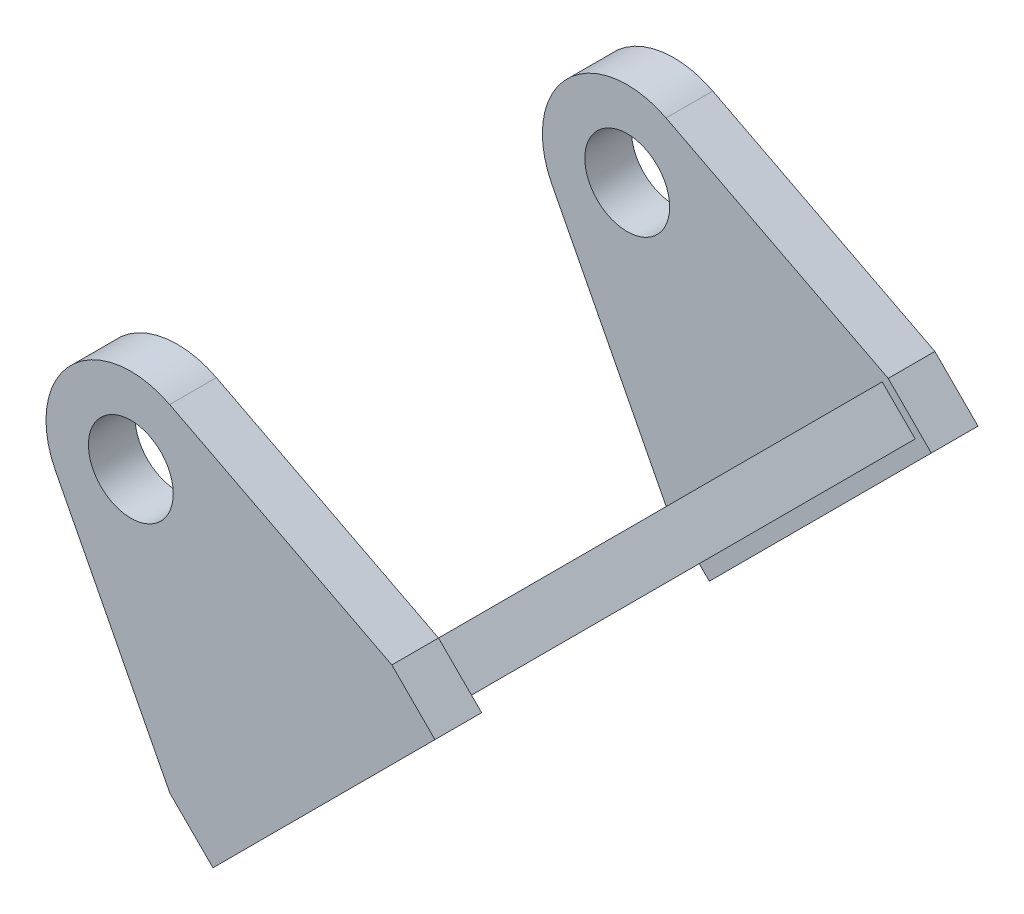
SolidWorks part; units mm, degrees
ref_plane "正面" through (0, 0, 0) normal (0, 0, 1) x (1, 0, 0)
ref_plane "平面" through (0, 0, 0) normal (0, 1, 0) x (1, 0, 0)
ref_plane "右側面" through (0, 0, 0) normal (1, 0, 0) x (0, 0, -1)
sketch "ｽｹｯﾁ1" plane through (0, 0, 0) normal (0, 0, 1) x (1, 0, 0)
  line L0 (0, 0) -> (3.8891, -3.8891)
  line L1 (0, 0) -> (24.7487, 24.7487)
  line L2 (3.8891, -3.8891) -> (28.6378, 20.8597)
  line L3 (24.7487, 24.7487) -> (28.6378, 20.8597)
  line L4 (0, 0) -> (23.4926, 0) construction
  dimension "D1" = 5.5
  dimension "D2" = 35
  dimension "D3" = 45
extrude "ﾎﾞｽ - 押し出し1" add sketch "ｽｹｯﾁ1" along normal mid plane 54
sketch "ｽｹｯﾁ3" plane through (0, 0, 27) normal (0, 0, 1) x (1, 0, 0)
  line L0 (-0.7071, -0.7071) -> (-14.1931, 25.4726)
  line L1 (-0.7239, 38.9419) -> (25.4558, 25.4558)
  line L2 (25.4558, 25.4558) -> (30.539, 20.3727)
  line L3 (30.539, 20.3727) -> (4.376, -5.7902)
  line L6 (28.6378, 20.8597) -> (24.7487, 24.7487) construction
  line L7 (24.7487, 24.7487) -> (0, 0) construction
  line L8 (-5.3033, 30.052) -> (12.3744, 12.3744) construction
  line L9 (-0.7071, -0.7071) -> (4.376, -5.7902)
  arc A0 (-14.1931, 25.4726) -> (-0.7239, 38.9419) centre (-5.3033, 30.052) cw
  circle A1 centre (-5.3033, 30.052) radius 5
  dimension "D3" = 10
  dimension "D4" = 10
  dimension "D1" = 1
  dimension "D5" = 25
extrude "ﾎﾞｽ - 押し出し2" add sketch "ｽｹｯﾁ3" along normal blind 5.5 from offset 0.5 separate body offset against normal yes
mirror "ﾐﾗｰ1" about plane through (0, 0, 0) normal (0, 0, 1) of bodies 102
sketch "ｽｹｯﾁ4" plane through (0, 0, 0) normal (-0.7071, 0.7071, 0) x (0, 0, 1)
  line L0 (0, 0) -> (0, 35) construction
  line L1 (27, 35) -> (-27, 35) construction
  line L2 (0, 17.5) -> (10.0083, 17.5) construction
  circle A0 centre (8, 28.5) radius 2.5
  circle A1 centre (-1, 6.5) radius 2.5
  point P11 (-1.5764, 6.5)
  dimension "D5" = 5
  dimension "D1" = 8
  dimension "D2" = 11
  dimension "D3" = 11
  dimension "D4" = 1
extrude "ｶｯﾄ - 押し出し1" cut sketch "ｽｹｯﾁ4" against normal blind 10
